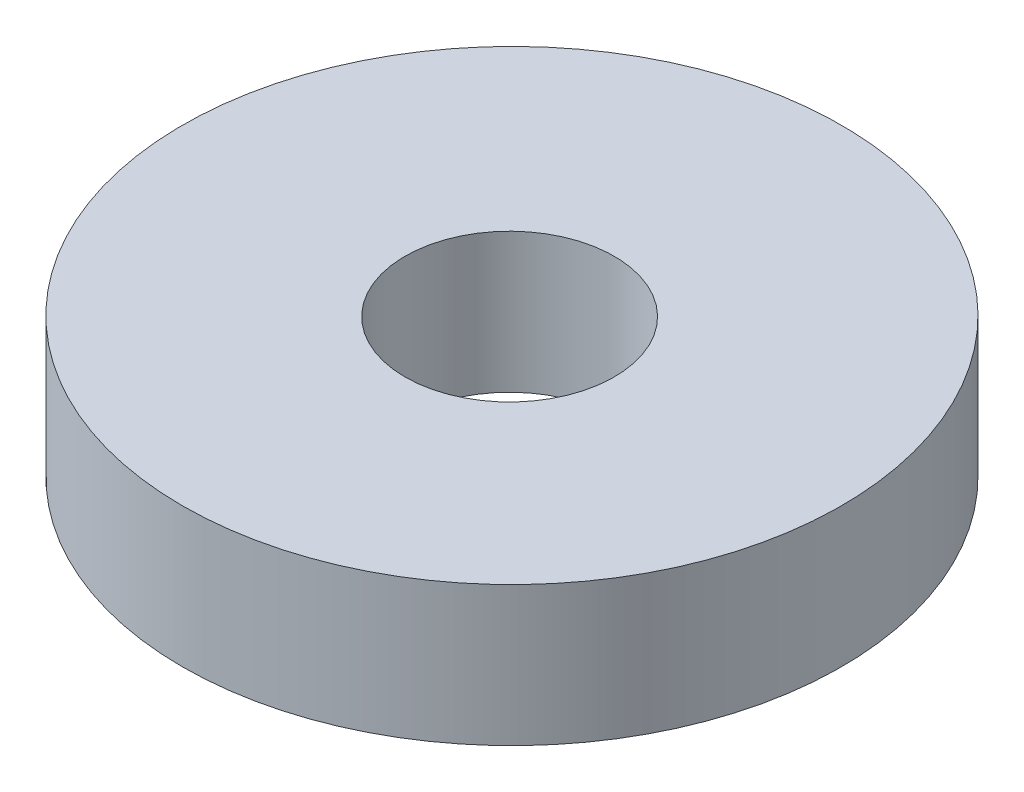
SolidWorks part; units mm, degrees
ref_plane "Front Plane" through (0, 0, 0) normal (0, 0, 1) x (1, 0, 0)
ref_plane "Top Plane" through (0, 0, 0) normal (0, 1, 0) x (1, 0, 0)
ref_plane "Right Plane" through (0, 0, 0) normal (1, 0, 0) x (0, 0, -1)
sketch "Sketch1" plane through (0, 0, 0) normal (0, 1, 0) x (1, 0, 0)
  circle A0 centre (0.0299, 0.3032) radius 47.25
  circle A1 centre (0, 0) radius 15
extrude "Boss-Extrude1" add sketch "Sketch1" along normal mid plane 20
sketch "Sketch2" plane through (0, -10, 0) normal (0, -1, 0) x (1, 0, 0)
  line L0 (-15, 0) -> (15, 0) construction
  line L1 (25, 0) -> (-25, 0) construction
  circle A0 centre (0, 0) radius 15 construction
  circle A1 centre (0, 0) radius 15 construction
  circle A2 centre (0, 0) radius 25 construction
  point P5 (0, 0)
  point P7 (-15, 0)
  point P8 (15, 0)
  point P11 (0, 0)
  point P13 (-25, 0)
  point P14 (25, 0)
  dimension "D1" = 50
sketch "Sketch3" plane through (0, 0, 0) normal (0, 0, 1) x (1, 0, 0)
  line L0 (-15, -10) -> (-15, -18)
  line L1 (-15, -18) -> (0, -18)
  line L3 (-18, -13) -> (-18, -21)
  line L4 (-18, -21) -> (0, -21)
  line L6 (-47.2201, -10) -> (47.2799, -10) construction
  line L7 (-25, -10) -> (-15, -10)
  line L8 (-25, -13) -> (-18, -13)
  line L9 (-25, -10) -> (-25, -13)
  line L10 (15, -10) -> (18, -10)
  line L11 (0, 0) -> (0, -21) construction
  line L12 (-47.2201, -10) -> (47.2799, -10) construction
  line L13 (-47.2201, -13) -> (47.2799, -13) construction
  line L14 (-18, -21) -> (18, -21) construction
  line L15 (-18, -10) -> (-18, -21) construction
  line L16 (-15, -18) -> (15, -18) construction
  line L17 (0, -21) -> (0, -18)
  line L18 (15, -18) -> (15, -10) construction
  line L19 (18, -21) -> (18, -10) construction
  dimension "D2" = 3
  dimension "D3" = 5
  dimension "D1" = 3
